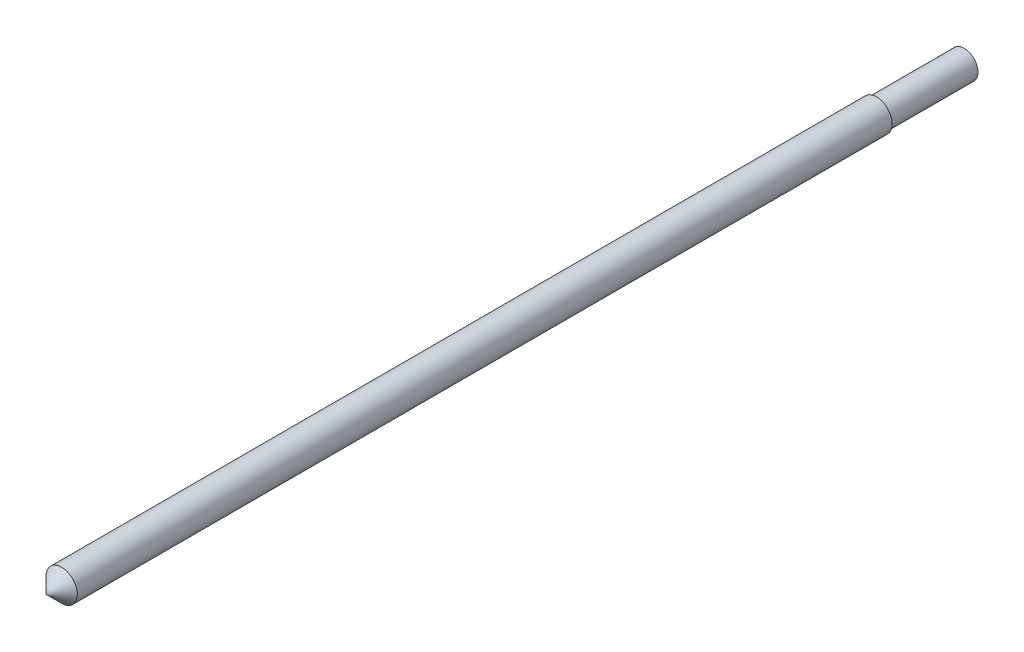
SolidWorks part; units mm, degrees
ref_plane "Front" through (0, 0, 0) normal (0, 0, 1) x (1, 0, 0)
ref_plane "Top" through (0, 0, 0) normal (0, 1, 0) x (1, 0, 0)
ref_plane "Right" through (0, 0, 0) normal (1, 0, 0) x (0, 0, -1)
sketch "Sketch1" plane through (0, 0, 0) normal (0, 0, 1) x (1, 0, 0)
  circle A0 centre (0, 0) radius 12.5
  dimension "D1" = 25
extrude "Boss-Extrude1" add sketch "Sketch1" along normal blind 650
sketch "Sketch2" plane through (0, 0, 0) normal (0, 1, 0) x (1, 0, 0)
  line L0 (0, -650) -> (0, -662.5)
  line L1 (-12.5, -650) -> (12.5, -650) construction
  line L2 (0, -662.5) -> (12.5, -650)
  line L3 (12.5, -650) -> (0, -650)
  dimension "D1" = 45
revolve "Revolve1" add sketch "Sketch2" angle 360 about L0
sketch "Sketch3" plane through (0, 0, 0) normal (0, 0, -1) x (-1, 0, 0)
  circle A0 centre (0, 0) radius 11
  dimension "D1" = 22
extrude "Boss-Extrude2" add sketch "Sketch3" along normal blind 70
